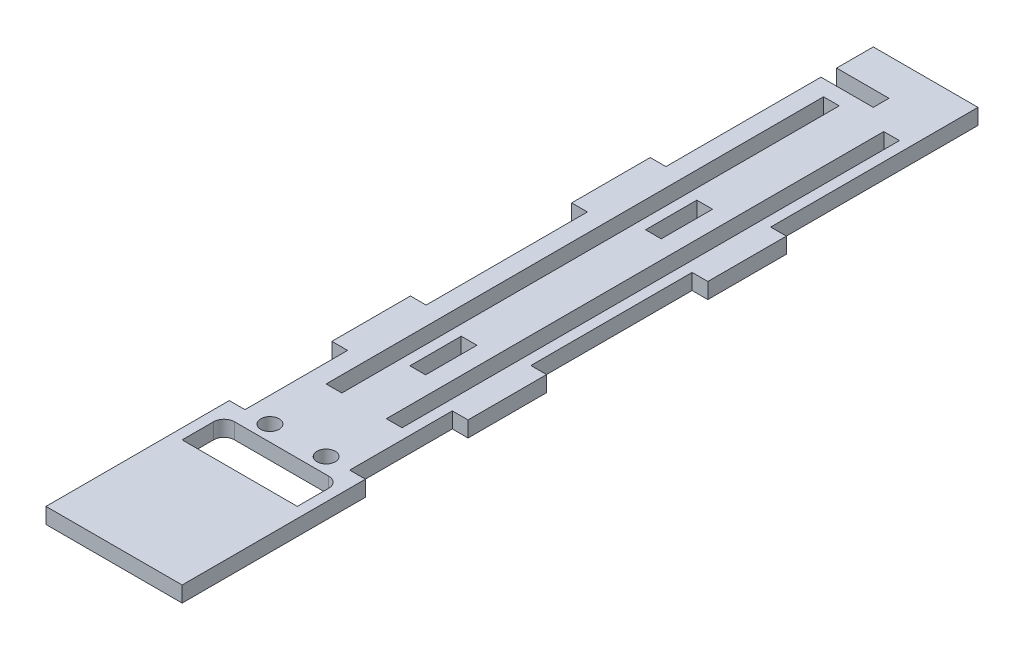
SolidWorks part; units mm, degrees
ref_plane "Спереди" through (0, 0, 0) normal (0, 0, 1) x (1, 0, 0)
ref_plane "Сверху" through (0, 0, 0) normal (0, 1, 0) x (1, 0, 0)
ref_plane "Справа" through (0, 0, 0) normal (1, 0, 0) x (0, 0, -1)
other "Configuration Table"
sketch "Эскиз2" plane through (0, 0, 0) normal (0, 1, 0) x (1, 0, 0)
  line L0 (-5.3024, 0) -> (5.3024, 0) construction
  line L1 (-10, -60) -> (10, -60)
  line L2 (-10, -60) -> (-10, -40.4)
  line L3 (-10, 60) -> (10, 60)
  line L4 (10, -60) -> (10, -40.4)
  line L5 (-10, -60) -> (10, 60) construction
  line L6 (-10, 60) -> (10, -60) construction
  line L7 (-10, 20.4) -> (-13, 20.4)
  line L9 (-10, 5.4) -> (-13, 5.4)
  line L10 (-13, 20.4) -> (-13, 5.4)
  line L11 (5.3024, 0) -> (0, 0) construction
  line L12 (0, -13.5509) -> (0, 13.5509) construction
  line L13 (13, 20.4) -> (13, 5.4)
  line L14 (10, 5.4) -> (13, 5.4)
  line L16 (10, 20.4) -> (13, 20.4)
  line L17 (13, -25.4) -> (13, -40.4)
  line L18 (-10, -25.4) -> (-13, -25.4)
  line L20 (-10, -40.4) -> (-13, -40.4)
  line L21 (-13, -25.4) -> (-13, -40.4)
  line L22 (10, -40.4) -> (13, -40.4)
  line L24 (10, -25.4) -> (13, -25.4)
  line L25 (-10, 20.4) -> (-10, 50)
  line L26 (10, 20.4) -> (10, 60)
  line L27 (-10, -25.4) -> (-10, 5.4)
  line L28 (10, -25.4) -> (10, 5.4)
  line L29 (-10, 53) -> (-10, 60)
  line L30 (-10, 53) -> (0, 53)
  line L32 (-10, 50) -> (0, 50)
  line L33 (0, 53) -> (0, 50)
  point P0 (0, 0)
  point P13 (0, 0)
  point P16 (0, 0)
  dimension "D1" = 20
  dimension "D2" = 120
  dimension "D3" = 3
  dimension "D4" = 15
  dimension "D5" = 54.6
  dimension "D6" = 3
  dimension "D7" = 15
  dimension "D8" = 19.6
  dimension "D9" = 10
  dimension "D10" = 3
  dimension "D11" = 7
extrude "Бобышка-Вытянуть1" add sketch "Эскиз2" along normal blind 3
sketch "Эскиз3" plane through (0, 3, 0) normal (0, 1, 0) x (1, 0, 0)
  line L0 (-10, -60) -> (10, -60) construction
  line L1 (-1.5, 8) -> (1.5, 8)
  line L2 (-1.5, 8) -> (-1.5, 17.8)
  line L3 (-1.5, 17.8) -> (1.5, 17.8)
  line L4 (1.5, 8) -> (1.5, 17.8)
  line L5 (-1.5, 8) -> (1.5, 17.8) construction
  line L6 (-1.5, 17.8) -> (1.5, 8) construction
  line L7 (-1.5, -37) -> (1.5, -37)
  line L8 (-1.5, -37) -> (-1.5, -27.2)
  line L9 (-1.5, -27.2) -> (1.5, -27.2)
  line L10 (1.5, -37) -> (1.5, -27.2)
  line L11 (-1.5, -37) -> (1.5, -27.2) construction
  line L12 (-1.5, -27.2) -> (1.5, -37) construction
  point P0 (0, 12.9)
  point P5 (0, -32.1)
  dimension "D1" = 3
  dimension "D2" = 9.8
  dimension "D3" = 0
  dimension "D4" = 3
  dimension "D5" = 9.8
  dimension "D6" = 0
  dimension "D7" = 23
  dimension "D8" = 68
extrude "Вырез-Вытянуть1" cut sketch "Эскиз3" against normal blind 10
sketch "Эскиз4" plane through (0, 0, 0) normal (0, -1, 0) x (1, 0, 0)
  line L1 (-13, 60) -> (13, 60)
  line L2 (-13, 60) -> (-13, 95)
  line L3 (-13, 95) -> (13, 95)
  line L4 (13, 60) -> (13, 95)
  dimension "D1" = 35
extrude "Бобышка-Вытянуть2" add sketch "Эскиз4" against normal up to surface (3 mm away) up to face at (0, 3, -12.9)
sketch "Эскиз5" plane through (0, 0, 0) normal (0, -1, 0) x (-1, 0, 0)
  line L0 (13, -60) -> (10, -60) construction
  line L1 (11, -63) -> (-11, -63)
  line L2 (11, -63) -> (11, -71)
  line L3 (11, -71) -> (-11, -71)
  line L4 (-11, -63) -> (-11, -71)
  line L5 (13, -95) -> (13, -60) construction
  dimension "D1" = 22
  dimension "D2" = 8
  dimension "D3" = 3
  dimension "D4" = 2
extrude "Вырез-Вытянуть2" cut sketch "Эскиз5" against normal blind 19
sketch "Эскиз6" plane through (0, 0, 0) normal (0, -1, 0) x (1, 0, 0)
  line L0 (10, 25.4) -> (10, -5.4) construction
  line L1 (8, -47) -> (5, -47)
  line L2 (8, -47) -> (8, 48)
  line L3 (8, 48) -> (5, 48)
  line L4 (5, -47) -> (5, 48)
  line L5 (10, -60) -> (-10, -60) construction
  dimension "D1" = 2
  dimension "D2" = 3
  dimension "D3" = 13
  dimension "D4" = 95
extrude "Вырез-Вытянуть3" cut sketch "Эскиз6" against normal blind 25
fillet "Скругление1" radius 2 2 edges at (11, 1.5, 63) (-11, 1.5, 63)
sketch "Эскиз7" plane through (0, 0, 0) normal (0, -1, 0) x (1, 0, 0)
  line L0 (10, 60) -> (10, 40.4) construction
  line L1 (-9, 63) -> (9, 63) construction
  circle A0 centre (5.5, 60) radius 1.75
  dimension "D3" = 3.5
  dimension "D1" = 4.5
  dimension "D2" = 3
extrude "Вырез-Вытянуть4" cut sketch "Эскиз7" against normal blind 10
sketch "Эскиз8" plane through (0, 0, 0) normal (0, -1, 0) x (1, 0, 0)
  line L0 (-1.5, 37) -> (-1.5, 27.2) construction
  line L1 (-6.5, 48) -> (-3.5, 48)
  line L2 (-6.5, 48) -> (-6.5, -47)
  line L3 (-6.5, -47) -> (-3.5, -47)
  line L4 (-3.5, 48) -> (-3.5, -47)
  line L7 (10, 60) -> (10, 40.4) construction
  circle A0 centre (-5.2297, 60) radius 1.75
  dimension "D3" = 3.5
  dimension "D1" = 2
  dimension "D2" = 3
  dimension "D4" = 15.2297
extrude "Вырез-Вытянуть5" cut sketch "Эскиз8" against normal blind 10
